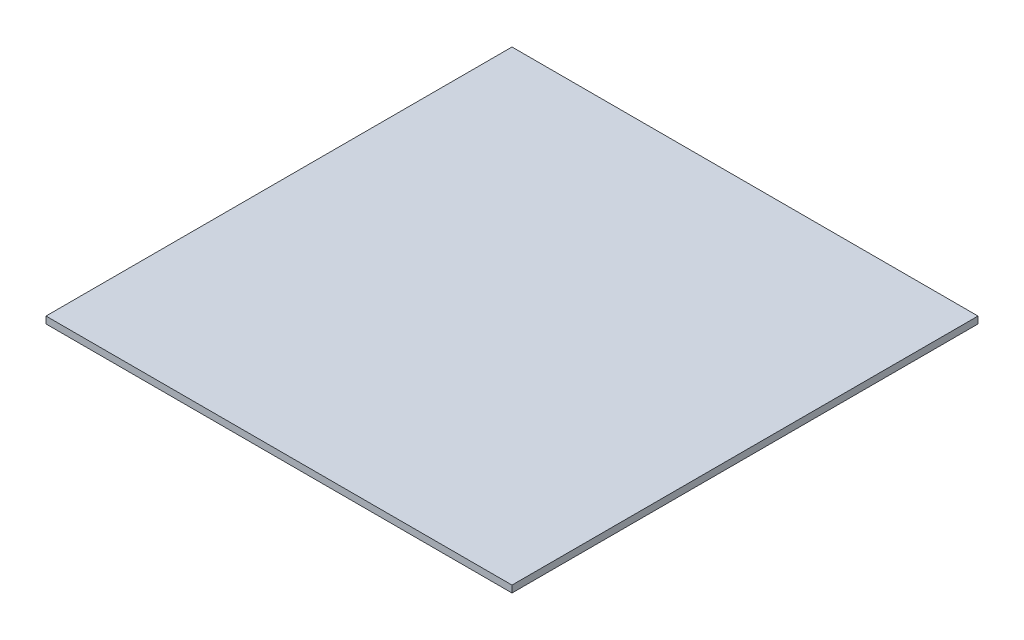
SolidWorks part; units mm, degrees
material "有机玻璃 (TM) GS 丙烯酸铸钣"
ref_plane "前视基准面" through (0, 0, 0) normal (0, 0, 1) x (1, 0, 0)
ref_plane "上视基准面" through (0, 0, 0) normal (0, 1, 0) x (1, 0, 0)
ref_plane "右视基准面" through (0, 0, 0) normal (1, 0, 0) x (0, 0, -1)
sketch "草图1" plane through (0, 0, 0) normal (0, 1, 0) x (1, 0, 0)
  line L1 (-101.5, 101.5) -> (101.5, 101.5)
  line L2 (-101.5, 101.5) -> (-101.5, -101.5)
  line L3 (-101.5, -101.5) -> (101.5, -101.5)
  line L4 (101.5, 101.5) -> (101.5, -101.5)
  line L5 (-101.5, 101.5) -> (101.5, -101.5) construction
  line L6 (-101.5, -101.5) -> (101.5, 101.5) construction
  point P0 (0, 0)
  dimension "D1" = 203
  dimension "D2" = 203
extrude "凸台-拉伸1" add sketch "草图1" along normal blind 3
